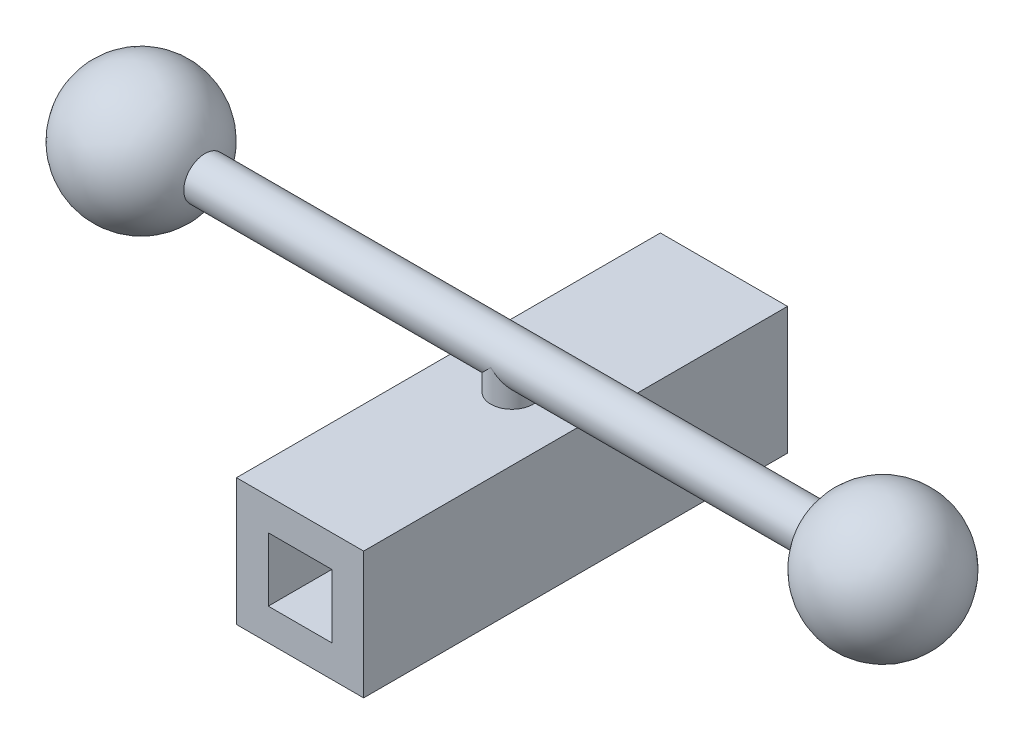
SolidWorks part; units mm, degrees
ref_plane "Plan de face" through (0, 0, 0) normal (0, 0, 1) x (1, 0, 0)
ref_plane "Plan de dessus" through (0, 0, 0) normal (0, 1, 0) x (1, 0, 0)
ref_plane "Plan de droite" through (0, 0, 0) normal (1, 0, 0) x (0, 0, -1)
sketch "Esquisse1" plane through (0, 0, 0) normal (0, 0, 1) x (1, 0, 0)
  line L0 (-3, 0) -> (3, 0) construction
  line L1 (-3, 3) -> (3, 3)
  line L2 (-3, 3) -> (-3, -3)
  line L3 (-3, -3) -> (3, -3)
  line L4 (3, 3) -> (3, -3)
  line L5 (0, 3) -> (0, -3) construction
  line L6 (-6, 6) -> (6, 6)
  line L7 (6, 6) -> (6, -6)
  line L8 (-6, -6) -> (6, -6)
  line L9 (-6, 6) -> (-6, -6)
  dimension "D1" = 6
  dimension "D2" = 6
  dimension "D3" = 3
extrude "Boss.-Extru.1" add sketch "Esquisse1" along normal mid plane 40
sketch3d "Esquisse3D2"
  line L0 (0, 6, 0) -> (0, 9, 0)
  line L1 (0, 9, 0) -> (-35, 9, 0)
  line L2 (-6, 6, 0) -> (6, 6, 0) construction
  dimension "D1" = 3
  dimension "D2" = 35
sketch "Esquisse2" plane through (0, 6, 0) normal (0, 1, 0) x (1, 0, 0)
  circle A0 centre (0, 0) radius 2
  dimension "D1" = 4
sweep "Balayage1" add profiles "Esquisse2" path "Esquisse3D2"
sketch "Esquisse3" plane through (0, 0, 0) normal (0, 0, 1) x (1, 0, 0)
  line L0 (-35, 11) -> (-35, 7) construction
  line L1 (-35, 15.35) -> (-35, 2.65) construction
  line L2 (-35, 15.35) -> (-35, 2.65)
  arc A0 (-35, 15.35) -> (-35, 2.65) centre (-35, 9) ccw
  dimension "D1" = 12.7
revolve "Révolution1" add sketch "Esquisse3" angle 360 about L1
mirror "Symétrie1" about plane through (0, 0, 0) normal (1, 0, 0) of "Révolution1", "Balayage1"
